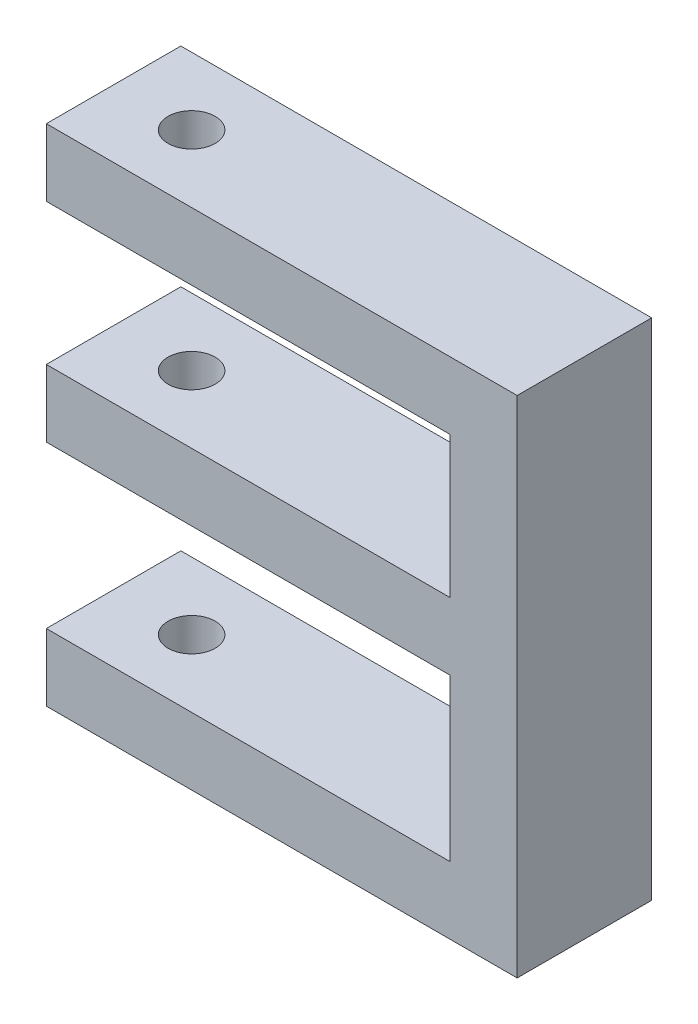
SolidWorks part; units mm, degrees
ref_plane "Ön Düzlem" through (0, 0, 0) normal (0, 0, 1) x (1, 0, 0)
ref_plane "Üst Düzlem" through (0, 0, 0) normal (0, 1, 0) x (1, 0, 0)
ref_plane "Sağ Düzlem" through (0, 0, 0) normal (1, 0, 0) x (0, 0, -1)
sketch "Çizim1" plane through (0, 0, 0) normal (0, 0, 1) x (1, 0, 0)
  line L0 (0, 0) -> (35, 0)
  line L1 (35, 0) -> (35, -37.5)
  line L2 (35, -37.5) -> (0, -37.5)
  line L3 (0, -37.5) -> (0, -32.5)
  line L4 (0, -32.5) -> (30, -32.5)
  line L5 (30, -32.5) -> (30, -5)
  line L6 (30, -5) -> (0, -5)
  line L7 (0, -5) -> (0, 0)
  dimension "D1" = 35
  dimension "D2" = 30
  dimension "D3" = 5
  dimension "D4" = 5
  dimension "D5" = 27.5
extrude "Yükseklik-Ekstrüzyon1" add sketch "Çizim1" along normal blind 10
sketch "Çizim2" plane through (0, 0, 0) normal (0, 1, 0) x (1, 0, 0)
  line L0 (35, -5) -> (7.5, -5)
  line L1 (35, -10) -> (35, 0) construction
  circle A0 centre (5.8, -5) radius 1.7
  dimension "D1" = 1.7
  dimension "D2" = 29.2
extrude "Kes-Ekstrüzyon1" cut sketch "Çizim2" against normal blind 47 contours A0
sketch "Çizim3" plane through (30, 0, 0) normal (-1, 0, 0) x (0, 0, 1)
  line L0 (0, -5) -> (0, -32.5) construction
  line L1 (0, -15.5) -> (10, -15.5)
  line L2 (0, -15.5) -> (0, -20.5)
  line L3 (0, -20.5) -> (10, -20.5)
  line L4 (10, -15.5) -> (10, -20.5)
  line L5 (10, -5) -> (10, -32.5) construction
  line L6 (10, -32.5) -> (0, -32.5) construction
  dimension "D1" = 5
  dimension "D2" = 12
extrude "Yükseklik-Ekstrüzyon2" add sketch "Çizim3" along normal up to surface (30 mm away) up to face at (0, -2.5, 5)
sketch "Çizim4" plane through (0, -15.5, 0) normal (0, 1, 0) x (1, 0, 0)
  circle A0 centre (5.8, -5) radius 1.75
extrude "Kes-Ekstrüzyon2" cut sketch "Çizim4" against normal blind 31 and the other way blind 31
